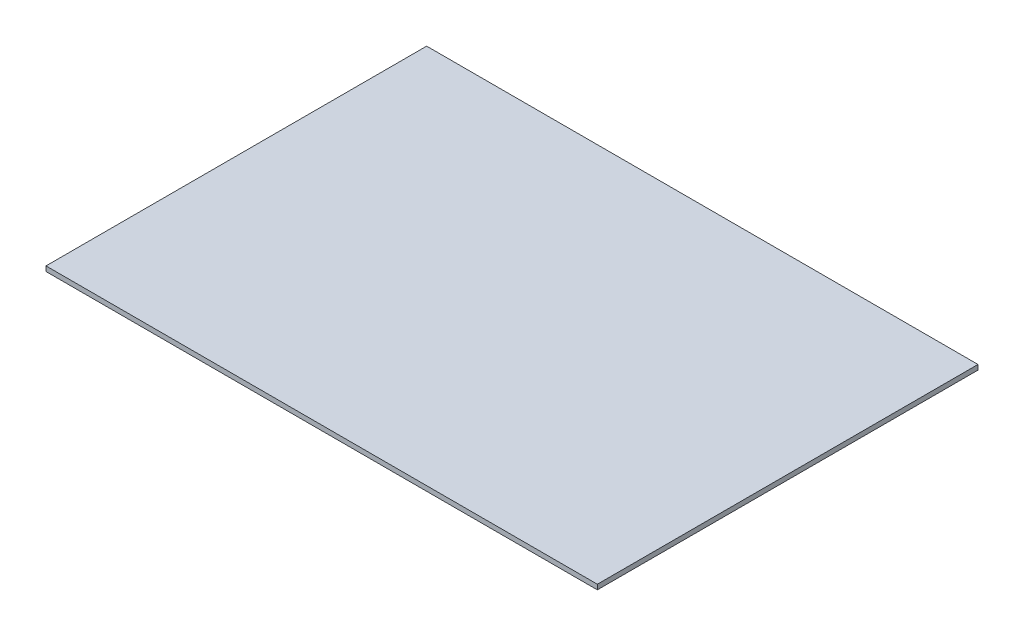
SolidWorks part; units mm, degrees
ref_plane "Front Plane" through (0, 0, 0) normal (0, 0, 1) x (1, 0, 0)
ref_plane "Top Plane" through (0, 0, 0) normal (0, 1, 0) x (1, 0, 0)
ref_plane "Right Plane" through (0, 0, 0) normal (1, 0, 0) x (0, 0, -1)
sketch "Sketch1" plane through (0, 0, 0) normal (0, 1, 0) x (1, 0, 0)
  line L1 (-140.5, -97) -> (140.5, -97)
  line L2 (-140.5, -97) -> (-140.5, 97)
  line L3 (-140.5, 97) -> (140.5, 97)
  line L4 (140.5, -97) -> (140.5, 97)
  line L5 (-140.5, -97) -> (140.5, 97) construction
  line L6 (-140.5, 97) -> (140.5, -97) construction
  point P0 (0, 0)
  dimension "D1" = 281
  dimension "D2" = 194
extrude "Extrude1" add sketch "Sketch1" along normal blind 2.5
